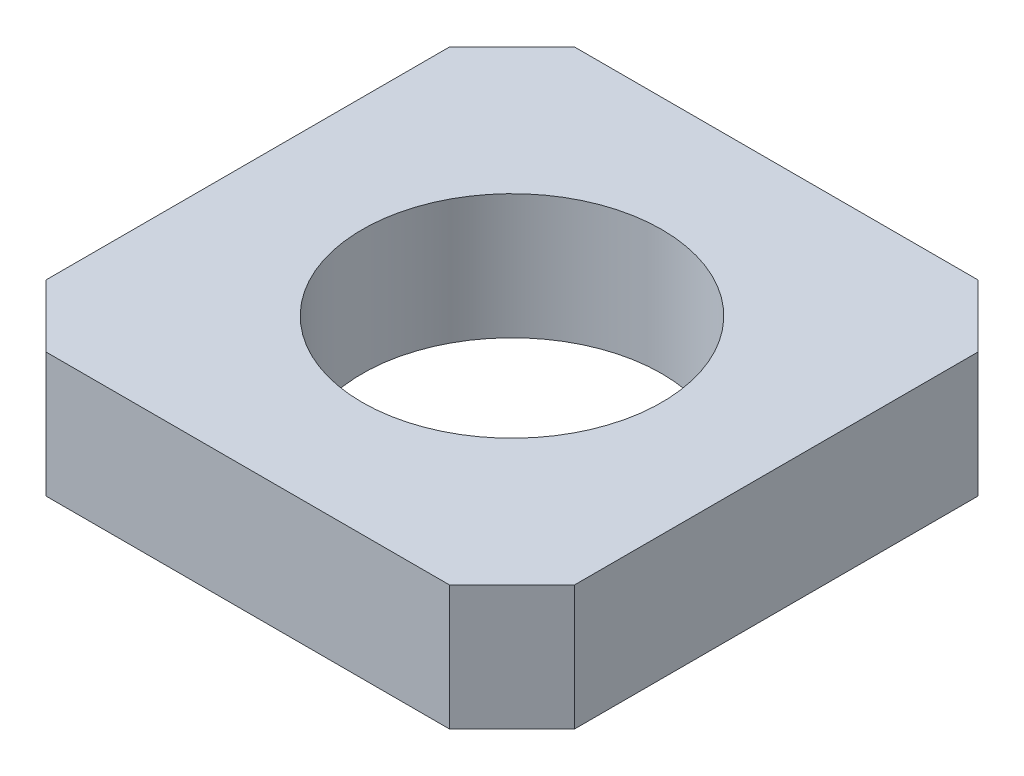
SolidWorks part; units mm, degrees
ref_plane "Front Plane" through (0, 0, 0) normal (0, 0, 1) x (1, 0, 0)
ref_plane "Top Plane" through (0, 0, 0) normal (0, 1, 0) x (1, 0, 0)
ref_plane "Right Plane" through (0, 0, 0) normal (1, 0, 0) x (0, 0, -1)
sketch "Sketch1" plane through (0, 0, 0) normal (0, 1, 0) x (1, 0, 0)
  circle A0 centre (0, 0) radius 12
  circle A1 centre (0, 0) radius 33.3348
extrude "Extrude1" add sketch "Sketch1" along normal blind 10
sketch "Sketch2" plane through (0, 0, 0) normal (0, -1, 0) x (1, 0, 0)
  line L0 (16.1693, 21.1693) -> (21.1693, 16.1693)
  line L1 (-21.1693, 16.1693) -> (-16.1693, 21.1693)
  line L2 (-16.1693, -21.1693) -> (-21.1693, -16.1693)
  line L3 (-16.1693, -21.1693) -> (16.1693, -21.1693)
  line L4 (-21.1693, -16.1693) -> (-21.1693, 16.1693)
  line L5 (-16.1693, 21.1693) -> (16.1693, 21.1693)
  line L6 (21.1693, -16.1693) -> (21.1693, 16.1693)
  line L7 (-21.1693, -21.1693) -> (21.1693, 21.1693) construction
  line L8 (-21.1693, 21.1693) -> (21.1693, -21.1693) construction
  line L9 (16.1693, -21.1693) -> (21.1693, -16.1693)
  line L17 (-34.3735, 34.3735) -> (34.3735, 34.3735)
  line L18 (-34.3735, 34.3735) -> (-34.3735, -34.3735)
  line L19 (-34.3735, -34.3735) -> (34.3735, -34.3735)
  line L20 (34.3735, 34.3735) -> (34.3735, -34.3735)
  line L21 (-34.3735, 34.3735) -> (34.3735, -34.3735) construction
  line L22 (-34.3735, -34.3735) -> (34.3735, 34.3735) construction
  point P3 (0, 0)
  point P17 (0, 0)
  dimension "D7" = 5
  dimension "D8" = 5
  dimension "D9" = 5
  dimension "D10" = 5
extrude "Cut-Extrude1" cut sketch "Sketch2" against normal blind 10
